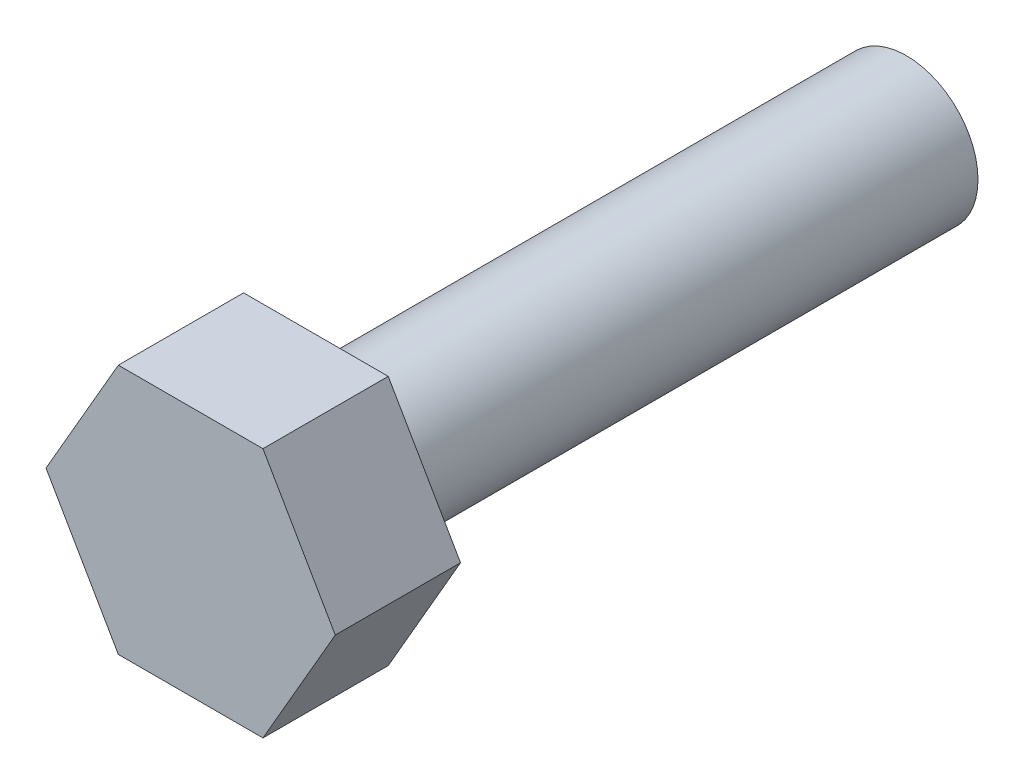
SolidWorks part; units mm, degrees
ref_plane "Front Plane" through (0, 0, 0) normal (0, 0, 1) x (1, 0, 0)
ref_plane "Top Plane" through (0, 0, 0) normal (0, 1, 0) x (1, 0, 0)
ref_plane "Right Plane" through (0, 0, 0) normal (1, 0, 0) x (0, 0, -1)
ref_plane "Plane1" through (0, 0, 1016) normal (0, 0, 1) x (1, 0, 0)
sketch "Sketch1" plane through (0, 0, 1016) normal (0, 0, 1) x (1, 0, 0)
  line L0 (-102.6529, -177.8) -> (102.6529, -177.8)
  line L1 (102.6529, -177.8) -> (205.3058, 0)
  line L2 (205.3058, 0) -> (102.6529, 177.8)
  line L3 (102.6529, 177.8) -> (-102.6529, 177.8)
  line L4 (-102.6529, 177.8) -> (-205.3058, 0)
  line L5 (-205.3058, 0) -> (-102.6529, -177.8)
extrude "Boss-Extrude1" add sketch "Sketch1" against normal blind 177.8
sketch "Sketch2" plane through (0, 0, 0) normal (0, 1, 0) x (1, 0, 0)
  line L0 (101.6, 0) -> (0, 0)
  line L1 (0, 0) -> (0, -838.2)
  line L2 (0, -838.2) -> (101.6, -838.2)
  line L3 (101.6, -838.2) -> (101.6, 0)
  line L4 (0, 0) -> (0, -838.2) construction
revolve "Revolve1" add sketch "Sketch2" angle 360 about L4
